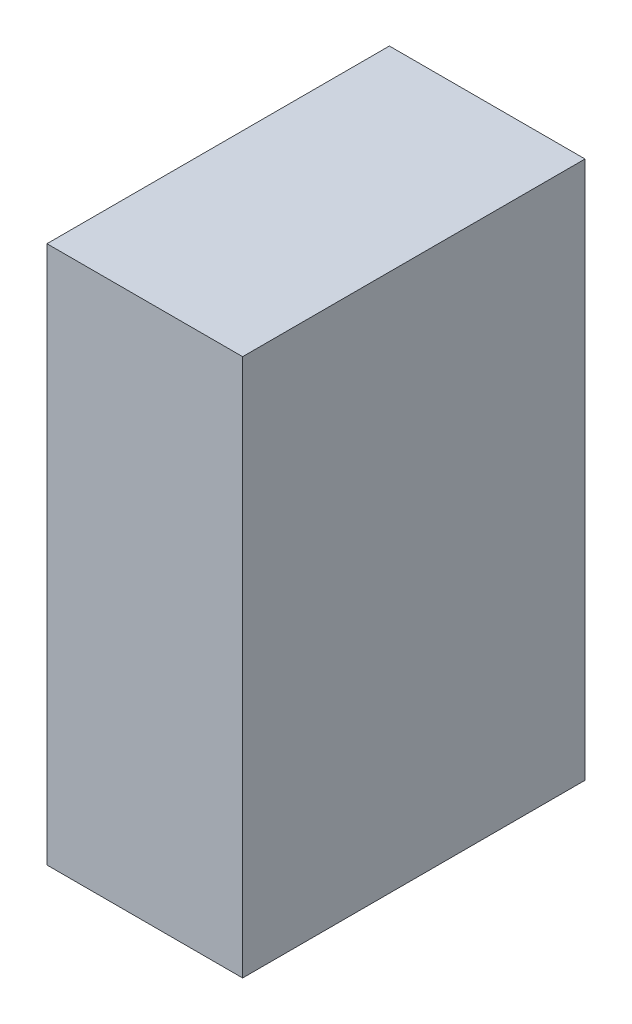
SolidWorks part; units mm, degrees
ref_plane "Plano frontal" through (0, 0, 0) normal (0, 0, 1) x (1, 0, 0)
ref_plane "Plano superior" through (0, 0, 0) normal (0, 1, 0) x (1, 0, 0)
ref_plane "Plano direito" through (0, 0, 0) normal (1, 0, 0) x (0, 0, -1)
sketch "Esboço1" plane through (0, 0, 0) normal (0, 0, 1) x (1, 0, 0)
  line L1 (0, 0) -> (101.6, 0)
  line L2 (0, 0) -> (0, 279.4)
  line L3 (0, 279.4) -> (101.6, 279.4)
  line L4 (101.6, 0) -> (101.6, 279.4)
extrude "Ressalto-extrusão1" add sketch "Esboço1" along normal blind 177.8 contours L3 L4 L1 L2
